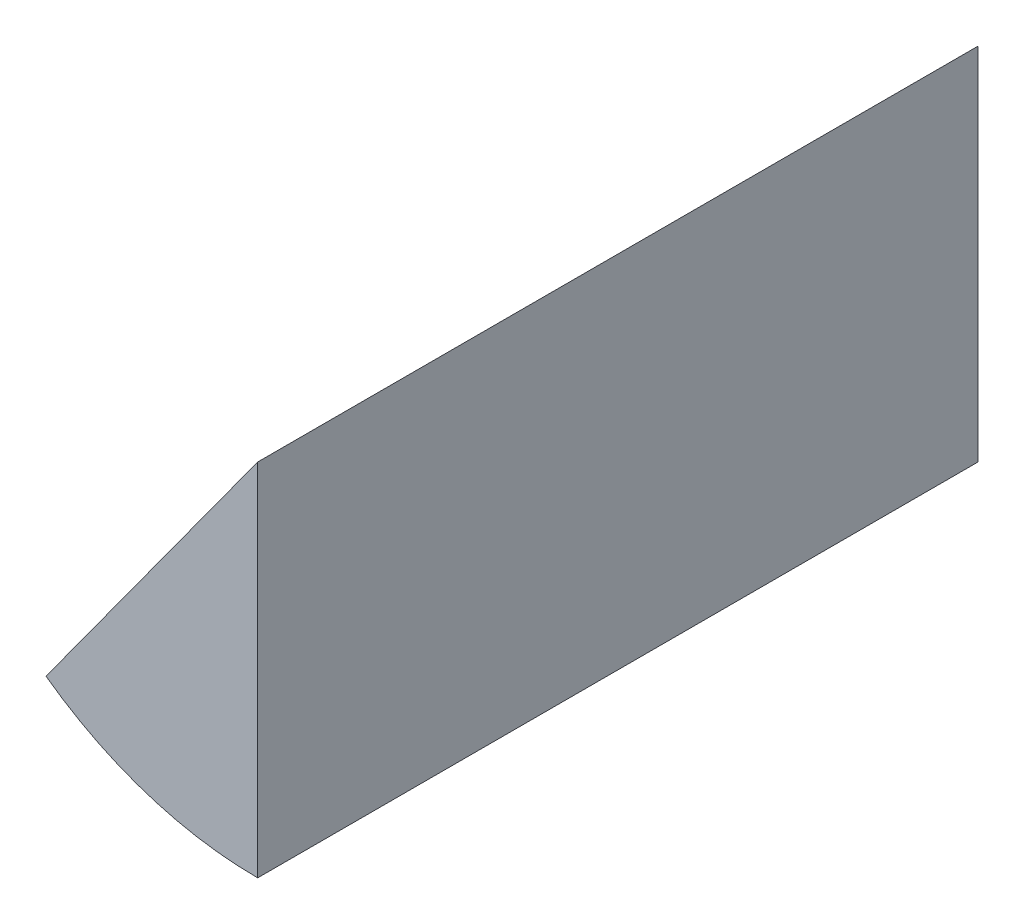
SolidWorks part; units mm, degrees
ref_plane "Alzado" through (0, 0, 0) normal (0, 0, 1) x (1, 0, 0)
ref_plane "Planta" through (0, 0, 0) normal (0, 1, 0) x (1, 0, 0)
ref_plane "Vista lateral" through (0, 0, 0) normal (1, 0, 0) x (0, 0, -1)
sketch "Croquis1" plane through (0, 0, 0) normal (0, 0, 1) x (1, 0, 0)
  line L0 (0, 0) -> (0, -25)
  line L1 (0, 0) -> (-14.6946, -20.2254)
  arc A0 (-14.6946, -20.2254) -> (0, -25) centre (0, 0) ccw
  dimension "D1" = 50
  dimension "D2" = 36
extrude "Saliente-Extruir1" add sketch "Croquis1" along normal blind 50
sketch "Croquis2" plane through (0, 0, 0) normal (0, 0, -1) x (-1, 0, 0)
  circle A0 centre (6.0539, -18.2632) radius 5.0032
extrude "Cortar-Extruir1" cut sketch "Croquis2" against normal blind 10
